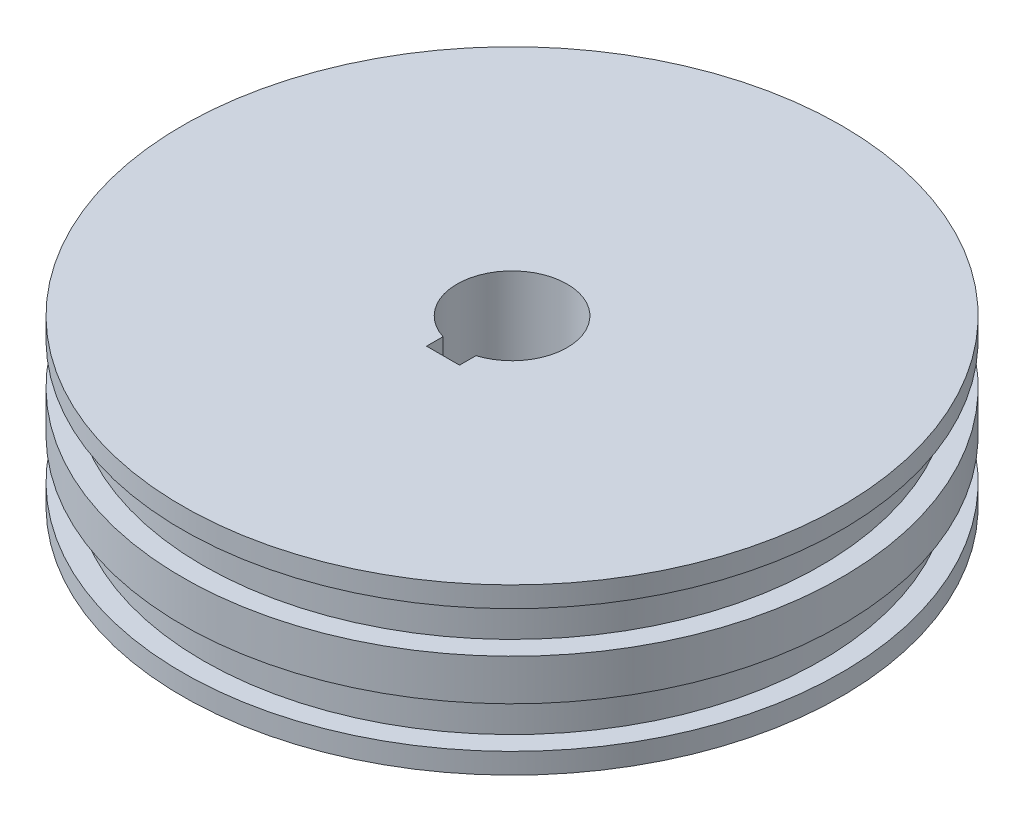
SolidWorks part; units mm, degrees
material "1023 Carbon Steel Sheet (SS)"
ref_plane "Front Plane" through (0, 0, 0) normal (0, 0, 1) x (1, 0, 0)
ref_plane "Top Plane" through (0, 0, 0) normal (0, 1, 0) x (1, 0, 0)
ref_plane "Right Plane" through (0, 0, 0) normal (1, 0, 0) x (0, 0, -1)
sketch "Sketch1" plane through (0, 0, 0) normal (1, 0, 0) x (0, 0, -1)
  line L0 (0, 0) -> (0, 35.2993) construction
  line L13 (10, 0) -> (80, 0)
  line L14 (80, 0) -> (80, 5)
  line L15 (80, 5) -> (75, 5)
  line L16 (75, 5) -> (75, 15)
  line L17 (75, 35) -> (80, 35)
  line L18 (80, 35) -> (80, 40)
  line L19 (80, 40) -> (10, 40)
  line L20 (10, 40) -> (10, 0)
  line L21 (75, 25) -> (75, 35)
  line L22 (75, 25) -> (80, 25)
  line L24 (75, 15) -> (80, 15)
  line L25 (80, 25) -> (80, 15)
  line L26 (71.8138, 24.8358) -> (80, 15) construction
  line L27 (70, 17.0152) -> (80, 25) construction
  point P5 (75, 21.0076)
  point P12 (77.5, 5)
  dimension "D1" = 10
  dimension "D2" = 75
  dimension "D3" = 5
  dimension "D4" = 5
revolve "Revolve1" add sketch "Sketch1" angle 360 about L0
sketch "Sketch2" plane through (0, 0, 0) normal (0, -1, 0) x (1, 0, 0)
  line L7 (-4, 16.7561) -> (4, 16.7561)
  line L8 (-4, 16.7561) -> (-4, 12.7561)
  line L9 (4, 16.7561) -> (4, 12.7561)
  line L10 (-4, 16.7561) -> (4, 12.7561) construction
  line L11 (-4, 12.7561) -> (4, 16.7561) construction
  arc A4 (-4, 12.7561) -> (4, 12.7561) centre (0, 0) ccw
  point P0 (0, 14.7561)
extrude "Cut-Extrude1" cut sketch "Sketch2" against normal through all
